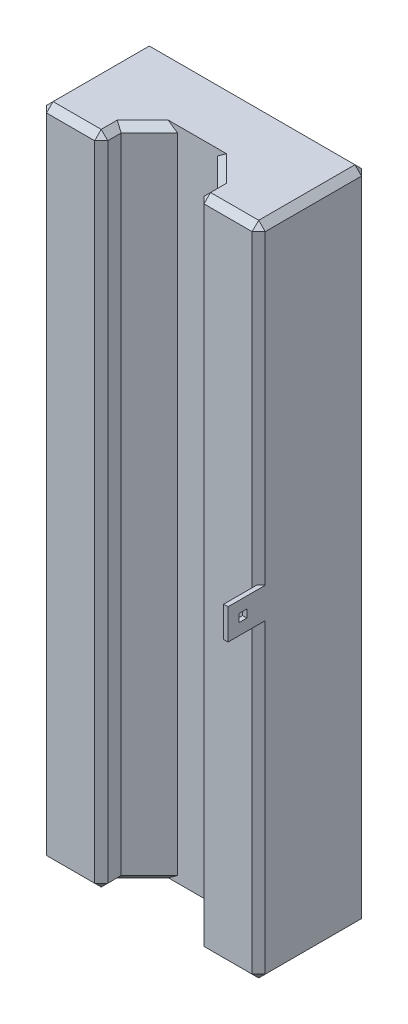
SolidWorks part; units mm, degrees
ref_plane "Front" through (0, 0, 0) normal (0, 0, 1) x (1, 0, 0)
ref_plane "Top" through (0, 0, 0) normal (0, 1, 0) x (1, 0, 0)
ref_plane "Right" through (0, 0, 0) normal (1, 0, 0) x (0, 0, -1)
sketch "Sketch1" plane through (0, 0, 0) normal (0, 0, 1) x (1, 0, 0)
  line L1 (0, 0) -> (50, 0)
  line L2 (0, 0) -> (0, 150)
  line L3 (0, 150) -> (50, 150)
  line L4 (50, 0) -> (50, 150)
  dimension "D1" = 50
  dimension "D2" = 150
extrude "Boss-Extrude1" add sketch "Sketch1" along normal blind 25
sketch "Sketch2" plane through (0, 0, 0) normal (0, -1, 0) x (1, 0, 0)
  line L0 (0, 25) -> (50, 25) construction
  line L1 (29.5563, 36) -> (20.4437, 36)
  line L2 (20.4437, 36) -> (14, 29.5563)
  line L3 (14, 29.5563) -> (14, 20.4437)
  line L4 (14, 20.4437) -> (20.4437, 14)
  line L5 (20.4437, 14) -> (29.5563, 14)
  line L6 (29.5563, 14) -> (36, 20.4437)
  line L7 (36, 20.4437) -> (36, 29.5563)
  line L8 (36, 29.5563) -> (29.5563, 36)
  circle A0 centre (25, 25) radius 11 construction
  dimension "D1" = 22
extrude "Cut-Extrude1" cut sketch "Sketch2" against normal through all
chamfer "Chamfer1" distance 1.5 angle 45 24 edges at (25, 150, 0) (0, 75, 0) (0, 150, 12.5) (32.7782, 150, 17.2218) (36, 150, 22.7218) (17.2218, 150, 17.2218) (7, 150, 25) (14, 150, 22.7218) (43, 150, 25) (50, 150, 12.5) (50, 75, 0) (14, 75, 25) (17.2218, 0, 17.2218) (14, 0, 22.7218) (7, 0, 25) (0, 75, 25) (0, 0, 12.5) (25, 0, 0) (50, 0, 12.5) (50, 75, 25) (43, 0, 25) (36, 75, 25) (32.7782, 0, 17.2218) (36, 0, 22.7218)
sketch "Sketch3" plane through (0, 0, 25) normal (0, 0, 1) x (1, 0, 0)
  line L0 (50, 148.5) -> (50, 1.5) construction
  line L1 (50, 78.5) -> (49, 78.5)
  line L2 (50, 78.5) -> (50, 71.5)
  line L3 (50, 71.5) -> (49, 71.5)
  line L4 (49, 78.5) -> (49, 71.5)
  point P6 (50, 75)
  dimension "D1" = 7
  dimension "D2" = 1
extrude "Boss-Extrude2" add sketch "Sketch3" along normal blind 7 and the other way blind 10
sketch "Sketch4" plane through (50, 0, 0) normal (1, 0, 0) x (0, 0, -1)
  line L0 (-29.5, 75) -> (-32, 75) construction
  line L1 (-29.5, 74.1) -> (-27.7, 74.1)
  line L2 (-29.5, 74.1) -> (-29.5, 75.9)
  line L3 (-29.5, 75.9) -> (-27.7, 75.9)
  line L4 (-27.7, 74.1) -> (-27.7, 75.9)
  line L5 (-32, 71.5) -> (-32, 78.5) construction
  dimension "D1" = 2.5
  dimension "D2" = 1.8
extrude "Cut-Extrude2" cut sketch "Sketch4" against normal blind 7
